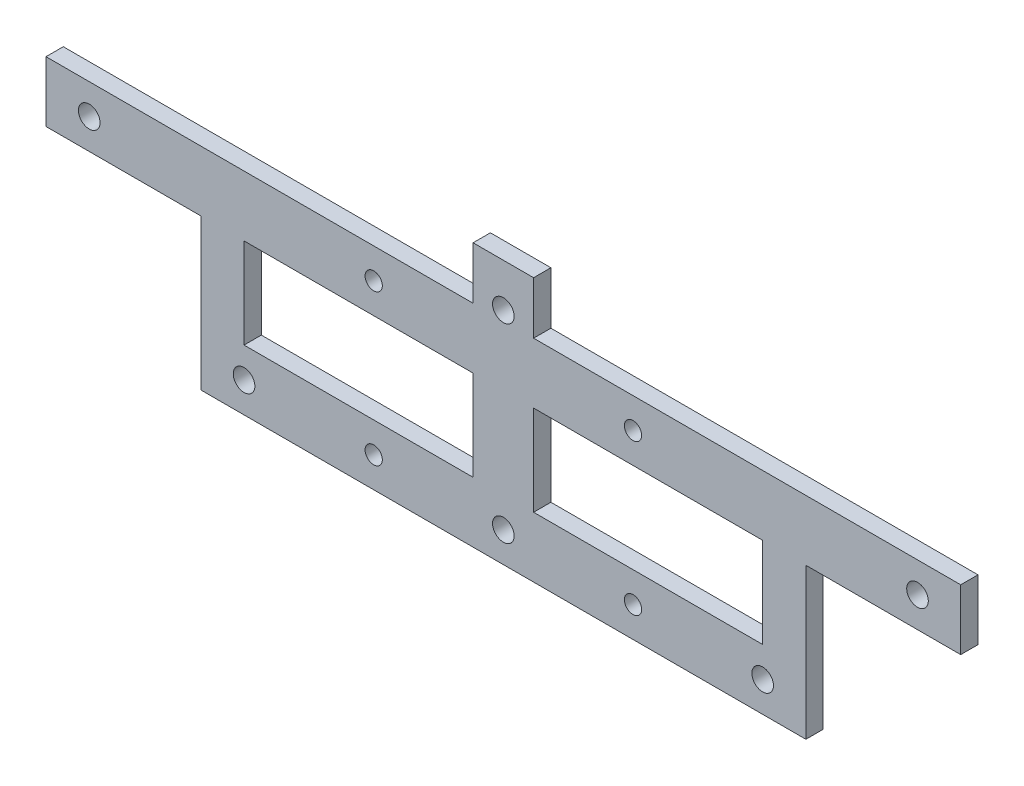
SolidWorks part; units mm, degrees
ref_plane "Front Plane" through (0, 0, 0) normal (0, 0, 1) x (1, 0, 0)
ref_plane "Top Plane" through (0, 0, 0) normal (0, 1, 0) x (1, 0, 0)
ref_plane "Right Plane" through (0, 0, 0) normal (1, 0, 0) x (0, 0, -1)
sketch "Sketch1" plane through (0, 0, 0) normal (0, 0, 1) x (1, 0, 0)
  line L0 (0, 0) -> (-60, 0) construction
  line L1 (0, 0) -> (60, 0) construction
  line L2 (0, 0) -> (-95.8264, 34.8779) construction
  line L3 (0, 0) -> (95.8264, 34.8779) construction
  line L4 (0, 0) -> (0, 44) construction
  line L6 (-70, 7) -> (70, 7)
  line L7 (-70, 7) -> (-70, -7)
  line L8 (-70, -7) -> (70, -7)
  line L9 (70, 7) -> (70, -7)
  line L10 (-7, 7) -> (7, 7)
  line L11 (-7, 7) -> (-7, 54)
  line L12 (-7, 54) -> (7, 54)
  line L13 (7, 7) -> (7, 54)
  line L14 (-105.8264, 27.8779) -> (-7, 27.8779)
  line L15 (-105.8264, 27.8779) -> (-105.8264, 41.8779)
  line L16 (-105.8264, 41.8779) -> (-7, 41.8779)
  line L17 (-7, 27.8779) -> (-7, 41.8779)
  line L18 (7, 41.8779) -> (105.8264, 41.8779)
  line L19 (7, 41.8779) -> (7, 27.8779)
  line L20 (7, 27.8779) -> (105.8264, 27.8779)
  line L21 (105.8264, 41.8779) -> (105.8264, 27.8779)
  line L22 (-70, 7) -> (-60, 7)
  line L23 (-70, 7) -> (-70, 27.8779)
  line L24 (-70, 27.8779) -> (-60, 27.8779)
  line L25 (-60, 7) -> (-60, 27.8779)
  line L26 (70, 7) -> (60, 7)
  line L27 (70, 7) -> (70, 27.8779)
  line L28 (70, 27.8779) -> (60, 27.8779)
  line L29 (60, 7) -> (60, 27.8779)
  circle A0 centre (-95.8264, 34.8779) radius 2.5
  circle A1 centre (0, 44) radius 2.5
  circle A2 centre (95.8264, 34.8779) radius 2.5
  circle A3 centre (60, 0) radius 2.5
  circle A4 centre (0, 0) radius 2.5
  circle A5 centre (-60, 0) radius 2.5
  circle A6 centre (-30, 34.8779) radius 2
  circle A7 centre (30, 34.8779) radius 2
  circle A8 centre (-30, 0) radius 2
  circle A9 centre (30, 0) radius 2
  dimension "D6" = 5
  dimension "D22" = 4
  dimension "D1" = 120
  dimension "D2" = 20
  dimension "D3" = 20
  dimension "D4" = 50
  dimension "D5" = 44
  dimension "D7" = 7
  dimension "D8" = 14
  dimension "D9" = 140
  dimension "D10" = 70
  dimension "D11" = 54
  dimension "D12" = 14
  dimension "D13" = 7
  dimension "D14" = 7
  dimension "D15" = 14
  dimension "D16" = 10
  dimension "D17" = 7
  dimension "D18" = 14
  dimension "D19" = 10
  dimension "D20" = 10
  dimension "D21" = 10
  dimension "D23" = 7
extrude "Boss-Extrude1" add sketch "Sketch1" along normal blind 4 contours L16 L15 L14 L11 A6 A0 | L6 L25 L14 L23 | L9 L6 L7 L8 A9 A8 A5 A4 A3 | L6 L13 L12 L11 A1 | L21 L18 L13 L20 A7 A2 | L29 L6 L27 L20
